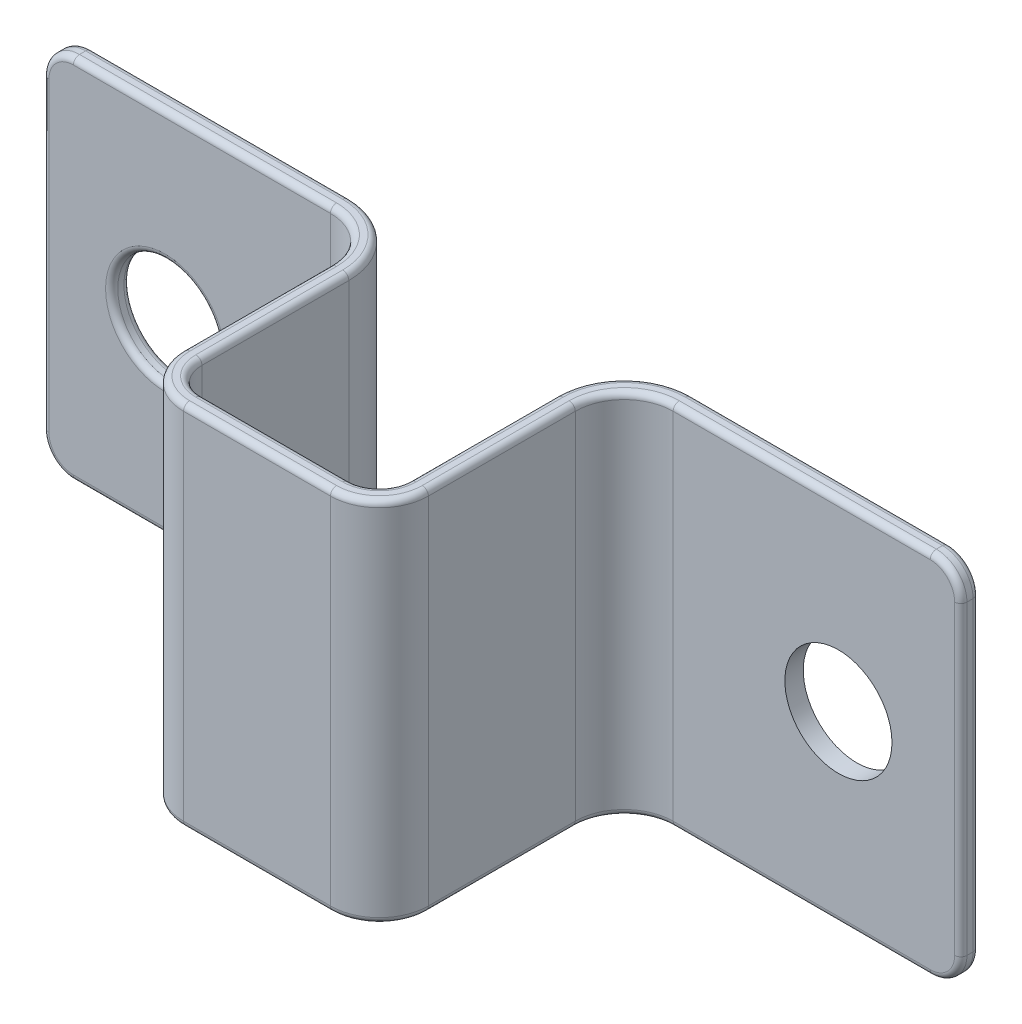
SolidWorks part; units mm, degrees
ref_plane "前视基准面" through (0, 0, 0) normal (0, 0, 1) x (1, 0, 0)
ref_plane "上视基准面" through (0, 0, 0) normal (0, 1, 0) x (1, 0, 0)
ref_plane "右视基准面" through (0, 0, 0) normal (1, 0, 0) x (0, 0, -1)
sketch "草图1" plane through (0, 0, 0) normal (0, 1, 0) x (1, 0, 0)
  line L0 (-15, 0) -> (-4, 0)
  line L1 (-4, 0) -> (-4, -8)
  line L2 (-4, -8) -> (4, -8)
  line L3 (4, -8) -> (4, 0)
  line L4 (4, 0) -> (15, 0)
  line L5 (0, 0) -> (0, -71.1958) construction
  line L6 (-15, 0.6) -> (-3.4, 0.6)
  line L7 (-3.4, 0.6) -> (-3.4, -7.4)
  line L8 (-3.4, -7.4) -> (3.4, -7.4)
  line L9 (3.4, -7.4) -> (3.4, 0.6)
  line L10 (3.4, 0.6) -> (15, 0.6)
  line L11 (15, 0.6) -> (15, 0)
  line L12 (-15, 0.6) -> (-15, 0)
  dimension "D1" = 30
  dimension "D2" = 8
  dimension "D3" = 8
  dimension "D4" = 0.6
extrude "凸台-拉伸1" add sketch "草图1" along normal mid plane 12
sketch "草图2" plane through (0, 0, 0) normal (0, 0, 1) x (1, 0, 0)
  line L0 (15, 6) -> (15, -6) construction
  circle A0 centre (-11, 0) radius 1.75
  circle A1 centre (11, 0) radius 1.75
  point P7 (15, 0)
  dimension "D1" = 22
  dimension "D2" = 3.5
  dimension "D3" = 11
extrude "切除-拉伸1" cut sketch "草图2" against normal up to surface (0.6 mm away) up to face at (-9.2, 0, -0.6)
fillet "圆角1" radius 1 2 edges at (3.4, 0, 7.4) (-3.4, 0, 7.4)
fillet "圆角2" radius 1.6 2 edges at (4, 0, 8) (-4, 0, 8)
fillet "圆角3" radius 1.6 2 edges at (4, 0, 0) (-4, 0, 0)
fillet "圆角4" radius 2.2 2 edges at (3.4, 0, -0.6) (-3.4, 0, -0.6)
fillet "圆角5" radius 1 4 edges at (-15, 6, -0.3) (-15, -6, -0.3) (15, -6, -0.3) (15, 6, -0.3)
fillet "圆角6" radius 0.2 50 edges at (-4.0444, 6, 0.0444) (-3.4, 6, 4) (-3.1071, 6, 7.1071) (0, 6, 7.4) (3.1071, 6, 7.1071) (3.4, 6, 4) (4.0444, 6, 0.0444) (9.8, 6, -0.6) (14.7071, 5.7071, -0.6) (15, 0, -0.6) (14.7071, -5.7071, -0.6) (9.8, -6, -0.6) (4.0444, -6, 0.0444) (3.4, -6, 4) (3.1071, -6, 7.1071) (0, -6, 7.4) (-3.1071, -6, 7.1071) (-3.4, -6, 4) (-4.0444, -6, 0.0444) (-4.4686, -6, 0.4686) (-4, -6, 4) (-3.5314, -6, 7.5314) (0, -6, 8) (3.5314, -6, 7.5314) (4, -6, 4) (4.4686, -6, 0.4686) (9.8, -6, 0) (14.7071, -5.7071, 0) (15, 0, 0) (14.7071, 5.7071, 0) (9.8, 6, 0) (4.4686, 6, 0.4686) (4, 6, 4) (3.5314, 6, 7.5314) (0, 6, 8) (-3.5314, 6, 7.5314) (-4, 6, 4) (-4.4686, 6, 0.4686) (-14.7071, -5.7071, -0.6) (-9.8, -6, -0.6) (-9.8, 6, -0.6) (-14.7071, 5.7071, -0.6) (-15, 0, -0.6) (-9.8, -6, 0) (-14.7071, -5.7071, 0) (-15, 0, 0) (-14.7071, 5.7071, 0) (-9.8, 6, 0) (-9.25, 0, -0.6) (-9.25, 0, 0)
